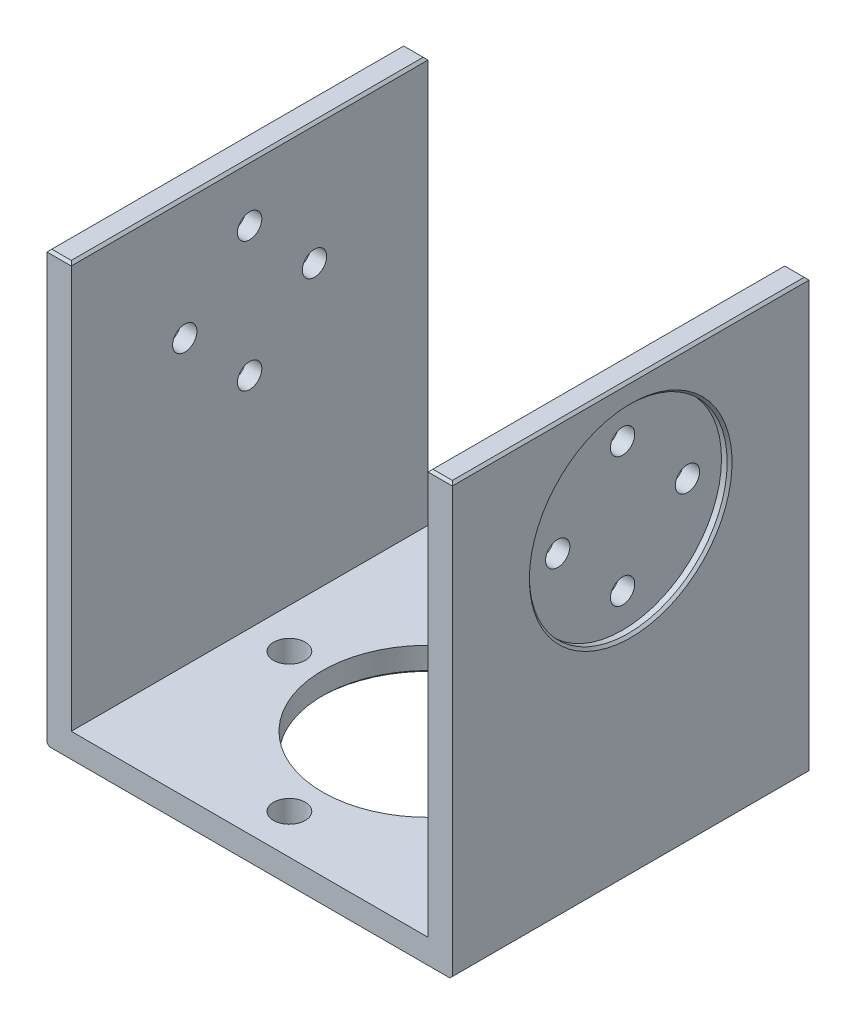
SolidWorks part; units mm, degrees
material "6061 合金"
ref_plane "前视基准面" through (0, 0, 0) normal (0, 0, 1) x (1, 0, 0)
ref_plane "上视基准面" through (0, 0, 0) normal (0, 1, 0) x (1, 0, 0)
ref_plane "右视基准面" through (0, 0, 0) normal (1, 0, 0) x (0, 0, -1)
sketch "草图1" plane through (0, 0, 0) normal (0, 1, 0) x (1, 0, 0)
  line L1 (-25, 22) -> (25, 22)
  line L2 (-25, 22) -> (-25, -22)
  line L3 (-25, -22) -> (25, -22)
  line L4 (25, 22) -> (25, -22)
  circle A0 centre (0, 0) radius 17.0961 construction
  circle A1 centre (0, 17.0961) radius 1.9538
  circle A2 centre (17.0961, 0) radius 1.9538
  circle A3 centre (0, -17.0961) radius 1.9538
  circle A4 centre (-17.0961, 0) radius 1.9538
  circle A5 centre (0, 0) radius 13
  point P14 (0, 0)
  dimension "D1" = 4
  dimension "D2" = 22
  dimension "D3" = 22
  dimension "D4" = 25
  dimension "D5" = 25
extrude "凸台-拉伸1" add sketch "草图1" along normal blind 3
sketch "草图2" plane through (0, 3, 0) normal (0, 1, 0) x (1, 0, 0)
  line L0 (-25, -22) -> (25, -22) construction
  line L1 (-25, 22) -> (-22, 22)
  line L2 (-25, 22) -> (-25, -22)
  line L3 (-25, -22) -> (-22, -22)
  line L4 (-22, 22) -> (-22, -22)
  line L6 (25, 22) -> (22, 22)
  line L7 (25, 22) -> (25, -22)
  line L8 (25, -22) -> (22, -22)
  line L9 (22, 22) -> (22, -22)
extrude "凸台-拉伸2" add sketch "草图2" along normal blind 50
sketch "草图3" plane through (-25, 0, 0) normal (-1, 0, 0) x (0, 0, 1)
  line L0 (22, 3) -> (-22, 3) construction
  line L1 (22, 3) -> (-22, 3) construction
  line L2 (0, 3) -> (0, 38) construction
  circle A0 centre (0, 38) radius 8 construction
  circle A1 centre (0, 46) radius 1.5
  circle A2 centre (8, 38) radius 1.5
  circle A3 centre (0, 30) radius 1.5
  circle A4 centre (-8, 38) radius 1.5
  point P17 (0, 38)
  dimension "D1" = 4
extrude "切除-拉伸1" cut sketch "草图3" against normal through all
sketch "草图4" plane through (25, 0, 0) normal (1, 0, 0) x (0, 0, -1)
  line L0 (0, 46) -> (0, 30) construction
  circle A0 centre (0, 38) radius 12.2
extrude "切除-拉伸2" cut sketch "草图4" against normal blind 1
mirror "镜向1" about plane through (0, 0, 0) normal (1, 0, 0) of "切除-拉伸2"
chamfer "倒角1" distance 0.3 angle 45 13 edges at (-25, 0, 0) (25, 0, 0) (-23.5, 53, -22) (-22, 53, 0) (-23.5, 53, 22) (-25, 53, 0) (23.5, 53, 22) (22, 53, 0) (23.5, 53, -22) (25, 53, 0) (-25, 38, -12.2) (25, 38, -12.2) (0, 0, 13)
